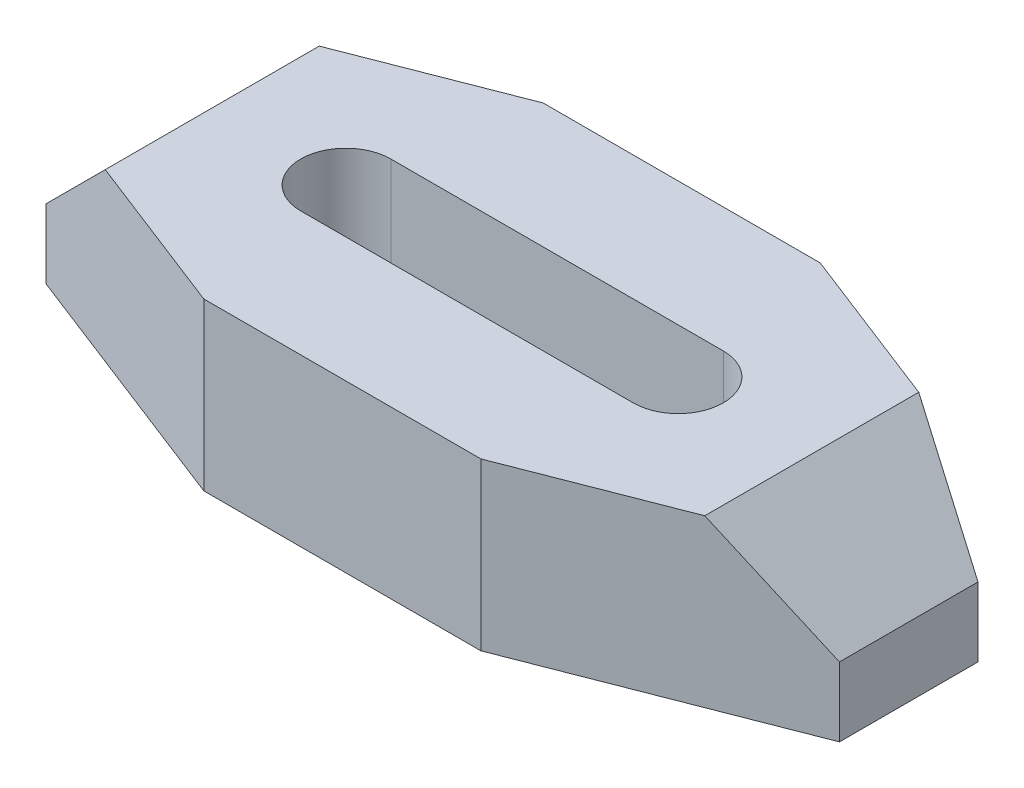
SolidWorks part; units mm, degrees
material "Cèdre"
ref_plane "Plan de face" through (0, 0, 0) normal (0, 0, 1) x (1, 0, 0)
ref_plane "Plan de dessus" through (0, 0, 0) normal (0, 1, 0) x (1, 0, 0)
ref_plane "Plan de droite" through (0, 0, 0) normal (1, 0, 0) x (0, 0, -1)
sketch "Esquisse2" plane through (0, 0, 0) normal (0, 1, 0) x (1, 0, 0)
  line L0 (-0.6044, 3.3177) -> (-4.6044, 3.3177)
  line L1 (-4.6044, 3.3177) -> (-8.3324, 1.8677)
  line L2 (-8.3324, 1.8677) -> (-8.3324, -0.1323)
  line L3 (-8.3324, 0.8677) -> (0.8831, 0.8677) construction
  line L4 (-4.6044, -1.5823) -> (-8.3324, -0.1323)
  line L5 (-0.6044, -1.5823) -> (-4.6044, -1.5823)
  line L6 (-2.6044, 2.3815) -> (-2.6044, -1.5823) construction
  line L7 (-0.2044, 1.5177) -> (-5.0044, 1.5177)
  line L8 (-0.2044, 0.2177) -> (-5.0044, 0.2177)
  line L9 (-0.6044, -1.5823) -> (3.1235, -0.1323)
  line L10 (3.1235, 1.8677) -> (3.1235, -0.1323)
  line L11 (-0.6044, 3.3177) -> (3.1235, 1.8677)
  arc A0 (-5.0044, 0.2177) -> (-5.0044, 1.5177) centre (-5.0044, 0.8677) cw
  arc A1 (-0.2044, 0.2177) -> (-0.2044, 1.5177) centre (-0.2044, 0.8677) ccw
  point P11 (-2.6044, 1.5177)
  point P17 (-2.6044, 0.2177)
  point P21 (-2.6044, 3.3177)
  dimension "D1" = 2
  dimension "D2" = 4
  dimension "D3" = 1
  dimension "D4" = 2.4
  dimension "D5" = 1.8
  dimension "D6" = 1.8
  dimension "D7" = 1.3
  dimension "D8" = 2.4
extrude "Boss.-Extru.2" add sketch "Esquisse2" along normal blind 2.4
chamfer "Chanfrein3" distance 1.4 angle 45 1 edges at (-8.3324, 2.4, -0.8677)
chamfer "Chanfrein4" distance 1.4 angle 45 1 edges at (3.1235, 2.4, -0.8677)
